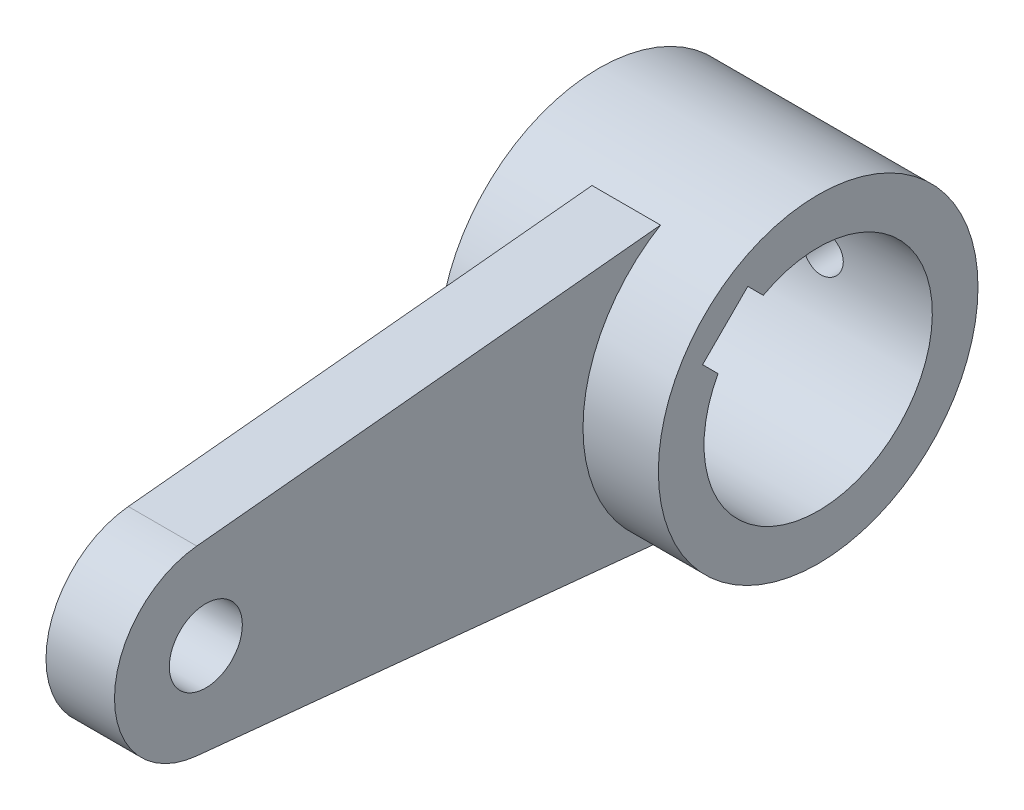
SolidWorks part; units mm, degrees
material "ASTM A36 Steel"
ref_plane "Front Plane" through (0, 0, 0) normal (0, 0, 1) x (1, 0, 0)
ref_plane "Top Plane" through (0, 0, 0) normal (0, 1, 0) x (1, 0, 0)
ref_plane "Right Plane" through (0, 0, 0) normal (1, 0, 0) x (0, 0, -1)
sketch "Sketch1" plane through (0, 0, 0) normal (1, 0, 0) x (0, 0, -1)
  circle A0 centre (0, 0) radius 25
  circle A1 centre (0, 0) radius 35
  dimension "D1" = 50
  dimension "D2" = 70
extrude "Boss-Extrude1" add sketch "Sketch1" along normal mid plane 48
sketch "Sketch2" plane through (0, 0, 0) normal (1, 0, 0) x (0, 0, -1)
  line L0 (-18.0278, 30) -> (-119.579, 19.9018)
  line L1 (-119.579, -19.9018) -> (-18.0278, -30)
  circle A0 centre (0, 0) radius 35 construction
  arc A1 (-119.579, 19.9018) -> (-119.579, -19.9018) centre (-117.6, 0) ccw
  circle A3 centre (0, 0) radius 35
  arc A4 (-18.0278, 30) -> (-18.0278, -30) centre (0, 0) ccw
  dimension "D2" = 20
  dimension "D1" = 117.6
  dimension "D3" = 60
  dimension "D4" = 0
extrude "Boss-Extrude2" add sketch "Sketch2" along normal mid plane 15
sketch "Sketch3" plane through (7.5, 0, 0) normal (1, 0, 0) x (0, 0, -1)
  circle A0 centre (-117.6, 0) radius 8
  dimension "D1" = 16
extrude "Cut-Extrude1" cut sketch "Sketch3" against normal blind 15
sketch "Sketch5" plane through (24, 0, 0) normal (1, 0, 0) x (0, 0, -1)
  line L0 (6.1966, 3.7029) -> (-15.4149, 25.3144)
  line L1 (6.1966, 3.7029) -> (-3.7029, -6.1966)
  line L2 (-15.4149, 25.3144) -> (-25.3144, 15.4149)
  line L3 (-3.7029, -6.1966) -> (-25.3144, 15.4149)
  line L4 (-20.3647, 20.3647) -> (1.2469, -1.2469) construction
  line L5 (-117.6, 0) -> (0, 0) construction
  dimension "D1" = 28.8
  dimension "D2" = 14
  dimension "D3" = 45
extrude "Cut-Extrude2" cut sketch "Sketch5" against normal through all
ref_plane "Plane1" through (0, 0, -35) normal (0, 0, 1) x (1, 0, 0)
sketch "Sketch6" plane through (0, 0, -35) normal (0, 0, 1) x (1, 0, 0)
  circle A0 centre (0, 0) radius 4.5
  dimension "D1" = 9
extrude "Cut-Extrude3" cut sketch "Sketch6" along normal blind 24
